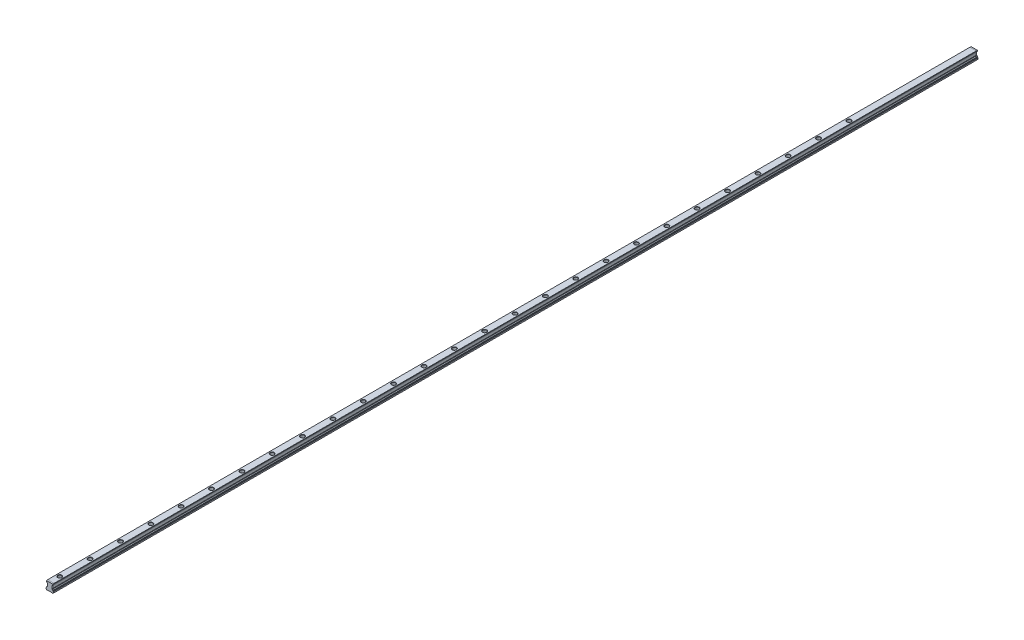
SolidWorks part; units mm, degrees
ref_plane "Front Plane" through (0, 0, 0) normal (0, 0, 1) x (1, 0, 0)
ref_plane "Top Plane" through (0, 0, 0) normal (0, 1, 0) x (1, 0, 0)
ref_plane "Right Plane" through (0, 0, 0) normal (1, 0, 0) x (0, 0, -1)
sketch "Sketch1" plane through (0, 0, 0) normal (0, 0, 1) x (1, 0, 0)
  line L0 (-4.6097, 4.7709) -> (-5.3042, 5.1719)
  line L1 (-4.6097, -0.4291) -> (-4.6097, 4.7709)
  line L2 (-5.3042, -0.83) -> (-4.6097, -0.4291)
  line L3 (-6.6597, -3.5791) -> (-6.6597, -2.0646)
  line L4 (-7.3597, -3.9832) -> (-6.6597, -3.5791)
  line L5 (-7.3597, -6.4791) -> (-7.3597, -3.9832)
  line L6 (-6.1597, -7.6791) -> (-7.3597, -6.4791)
  line L7 (-3.1597, -7.6791) -> (-6.1597, -7.6791)
  line L8 (-2.8597, -7.3791) -> (-3.1597, -7.6791)
  line L9 (3.1403, -7.3791) -> (-2.8597, -7.3791)
  line L10 (3.4403, -7.6791) -> (3.1403, -7.3791)
  line L11 (6.4403, -7.6791) -> (3.4403, -7.6791)
  line L12 (7.6403, -6.4791) -> (6.4403, -7.6791)
  line L13 (7.6403, -3.9832) -> (7.6403, -6.4791)
  line L14 (6.9403, -3.5791) -> (7.6403, -3.9832)
  line L15 (6.9403, -2.0646) -> (6.9403, -3.5791)
  line L16 (4.8903, -0.4291) -> (5.5848, -0.83)
  line L17 (4.8903, 4.7709) -> (4.8903, -0.4291)
  line L18 (5.5848, 5.1719) -> (4.8903, 4.7709)
  line L19 (6.9403, 8.0259) -> (6.9403, 6.4065)
  line L20 (6.4453, 8.5209) -> (6.9403, 8.0259)
  line L21 (-6.1647, 8.5209) -> (6.4453, 8.5209)
  line L22 (-6.6597, 8.0259) -> (-6.1647, 8.5209)
  line L23 (-6.6597, 6.4065) -> (-6.6597, 8.0259)
  arc A0 (-5.3042, 5.1719) -> (-6.6597, 6.4065) centre (-6.9057, 4.7749) ccw
  arc A1 (-6.6597, -2.0646) -> (-5.3042, -0.83) centre (-6.9057, -0.4331) ccw
  arc A2 (5.5848, -0.83) -> (6.9403, -2.0646) centre (7.1863, -0.4331) ccw
  arc A3 (6.9403, 6.4065) -> (5.5848, 5.1719) centre (7.1863, 4.7749) ccw
  dimension "Rail Height" = 16.2
  dimension "Rail Width" = 15
sketch "Sketch2" plane through (0, 0, 0) normal (1, 0, 0) x (0, 0, -1)
  line L0 (-914, 0) -> (914, 0) construction
  line L1 (-774, 0) -> (-774, -10.3) construction
  point P0 (-894, 0)
  point P4 (0, 0)
  point P6 (-834, 0)
  point P7 (-774, 0)
  point P9 (-714, 0)
  point P10 (-654, 0)
  point P11 (-594, 0)
  point P12 (-534, 0)
  point P13 (-474, 0)
  point P14 (-414, 0)
  point P15 (-354, 0)
  point P16 (-294, 0)
  point P17 (-234, 0)
  point P18 (-174, 0)
  point P19 (-114, 0)
  point P20 (-54, 0)
  point P21 (6, 0)
  point P22 (66, 0)
  point P23 (126, 0)
  point P24 (186, 0)
  point P25 (246, 0)
  point P26 (306, 0)
  point P27 (366, 0)
  point P28 (426, 0)
  point P29 (486, 0)
  point P30 (546, 0)
  point P31 (606, 0)
  point P32 (666, 0)
  dimension "Rail Length" = 1828
  dimension "Mounting Hole Center to End" = 20
  dimension "Mounting Hole Center to Center" = 60
  dimension "Mounting Hole Depth" = 10.3
  dimension "Number of Mounting Holes" = 27
sketch "Sketch3" plane through (0, 0, 0) normal (0, 0, 1) x (1, 0, 0)
  line L24 (6.4403, -7.6791) -> (7.6403, -6.4791)
  line L25 (7.6403, -6.4791) -> (7.6403, -3.9832)
  line L26 (7.6403, -3.9832) -> (6.9403, -3.5791)
  line L27 (6.9403, -3.5791) -> (6.9403, -2.0646)
  line L28 (5.5848, -0.83) -> (4.8903, -0.4291)
  line L29 (4.8903, -0.4291) -> (4.8903, 4.7709)
  line L30 (4.8903, 4.7709) -> (5.5848, 5.1719)
  line L31 (6.9403, 6.4065) -> (6.9403, 8.0259)
  line L32 (6.9403, 8.0259) -> (6.4453, 8.5209)
  line L33 (6.4453, 8.5209) -> (-6.1647, 8.5209)
  line L34 (-6.1647, 8.5209) -> (-6.6597, 8.0259)
  line L35 (-6.6597, 8.0259) -> (-6.6597, 6.4065)
  line L36 (-5.3042, 5.1719) -> (-4.6097, 4.7709)
  line L37 (-4.6097, 4.7709) -> (-4.6097, -0.4291)
  line L38 (-4.6097, -0.4291) -> (-5.3042, -0.83)
  line L39 (-6.6597, -2.0646) -> (-6.6597, -3.5791)
  line L40 (-6.6597, -3.5791) -> (-7.3597, -3.9832)
  line L41 (-7.3597, -3.9832) -> (-7.3597, -6.4791)
  line L42 (-7.3597, -6.4791) -> (-6.1597, -7.6791)
  line L43 (-6.1597, -7.6791) -> (-3.1597, -7.6791)
  line L44 (-3.1597, -7.6791) -> (-2.8597, -7.3791)
  line L45 (-2.8597, -7.3791) -> (3.1403, -7.3791)
  line L46 (3.1403, -7.3791) -> (3.4403, -7.6791)
  line L47 (3.4403, -7.6791) -> (6.4403, -7.6791)
  line L48 (6.4403, -7.6791) -> (7.6403, -6.4791)
  line L49 (7.6403, -6.4791) -> (7.6403, -3.9832)
  line L50 (7.6403, -3.9832) -> (6.9403, -3.5791)
  line L51 (6.9403, -3.5791) -> (6.9403, -2.0646)
  line L52 (5.5848, -0.83) -> (4.8903, -0.4291)
  line L53 (4.8903, -0.4291) -> (4.8903, 4.7709)
  line L54 (4.8903, 4.7709) -> (5.5848, 5.1719)
  line L55 (6.9403, 6.4065) -> (6.9403, 8.0259)
  line L56 (6.9403, 8.0259) -> (6.4453, 8.5209)
  line L57 (6.4453, 8.5209) -> (-6.1647, 8.5209)
  line L58 (-6.1647, 8.5209) -> (-6.6597, 8.0259)
  line L59 (-6.6597, 8.0259) -> (-6.6597, 6.4065)
  line L60 (-5.3042, 5.1719) -> (-4.6097, 4.7709)
  line L61 (-4.6097, 4.7709) -> (-4.6097, -0.4291)
  line L62 (-4.6097, -0.4291) -> (-5.3042, -0.83)
  line L63 (-6.6597, -2.0646) -> (-6.6597, -3.5791)
  line L64 (-6.6597, -3.5791) -> (-7.3597, -3.9832)
  line L65 (-7.3597, -3.9832) -> (-7.3597, -6.4791)
  line L66 (-7.3597, -6.4791) -> (-6.1597, -7.6791)
  line L67 (-6.1597, -7.6791) -> (-3.1597, -7.6791)
  line L68 (-3.1597, -7.6791) -> (-2.8597, -7.3791)
  line L69 (-2.8597, -7.3791) -> (3.1403, -7.3791)
  line L70 (3.1403, -7.3791) -> (3.4403, -7.6791)
  line L71 (3.4403, -7.6791) -> (6.4403, -7.6791)
  arc A4 (5.5848, -0.83) -> (6.9403, -2.0646) centre (7.1863, -0.4331) ccw
  arc A5 (6.9403, 6.4065) -> (5.5848, 5.1719) centre (7.1863, 4.7749) ccw
  arc A6 (-5.3042, 5.1719) -> (-6.6597, 6.4065) centre (-6.9057, 4.7749) ccw
  arc A7 (-6.6597, -2.0646) -> (-5.3042, -0.83) centre (-6.9057, -0.4331) ccw
  arc A8 (5.5848, -0.83) -> (6.9403, -2.0646) centre (7.1863, -0.4331) ccw
  arc A9 (6.9403, 6.4065) -> (5.5848, 5.1719) centre (7.1863, 4.7749) ccw
  arc A10 (-5.3042, 5.1719) -> (-6.6597, 6.4065) centre (-6.9057, 4.7749) ccw
  arc A11 (-6.6597, -2.0646) -> (-5.3042, -0.83) centre (-6.9057, -0.4331) ccw
  dimension "D1" = 0
extrude "Boss-Extrude1" add sketch "Sketch3" along normal mid plane 1823
sketch "Sketch4" plane through (0, 0, 911.5) normal (0, 0, 1) x (1, 0, 0)
  line L24 (6.4403, -7.6791) -> (7.6403, -6.4791)
  line L25 (7.6403, -6.4791) -> (7.6403, -3.9832)
  line L26 (7.6403, -3.9832) -> (6.9403, -3.5791)
  line L27 (6.9403, -3.5791) -> (6.9403, -2.0646)
  line L28 (5.5848, -0.83) -> (4.8903, -0.4291)
  line L29 (4.8903, -0.4291) -> (4.8903, 4.7709)
  line L30 (4.8903, 4.7709) -> (5.5848, 5.1719)
  line L31 (6.9403, 6.4065) -> (6.9403, 8.0259)
  line L32 (6.9403, 8.0259) -> (6.4453, 8.5209)
  line L33 (6.4453, 8.5209) -> (-6.1647, 8.5209)
  line L34 (-6.1647, 8.5209) -> (-6.6597, 8.0259)
  line L35 (-6.6597, 8.0259) -> (-6.6597, 6.4065)
  line L36 (-5.3042, 5.1719) -> (-4.6097, 4.7709)
  line L37 (-4.6097, 4.7709) -> (-4.6097, -0.4291)
  line L38 (-4.6097, -0.4291) -> (-5.3042, -0.83)
  line L39 (-6.6597, -2.0646) -> (-6.6597, -3.5791)
  line L40 (-6.6597, -3.5791) -> (-7.3597, -3.9832)
  line L41 (-7.3597, -3.9832) -> (-7.3597, -6.4791)
  line L42 (-7.3597, -6.4791) -> (-6.1597, -7.6791)
  line L43 (-6.1597, -7.6791) -> (-3.1597, -7.6791)
  line L44 (-3.1597, -7.6791) -> (-2.8597, -7.3791)
  line L45 (-2.8597, -7.3791) -> (3.1403, -7.3791)
  line L46 (3.1403, -7.3791) -> (3.4403, -7.6791)
  line L47 (3.4403, -7.6791) -> (6.4403, -7.6791)
  line L48 (6.4403, -7.6791) -> (7.6403, -6.4791)
  line L49 (7.6403, -6.4791) -> (7.6403, -3.9832)
  line L50 (7.6403, -3.9832) -> (6.9403, -3.5791)
  line L51 (6.9403, -3.5791) -> (6.9403, -2.0646)
  line L52 (5.5848, -0.83) -> (4.8903, -0.4291)
  line L53 (4.8903, -0.4291) -> (4.8903, 4.7709)
  line L54 (4.8903, 4.7709) -> (5.5848, 5.1719)
  line L55 (6.9403, 6.4065) -> (6.9403, 8.0259)
  line L56 (6.9403, 8.0259) -> (6.4453, 8.5209)
  line L57 (6.4453, 8.5209) -> (-6.1647, 8.5209)
  line L58 (-6.1647, 8.5209) -> (-6.6597, 8.0259)
  line L59 (-6.6597, 8.0259) -> (-6.6597, 6.4065)
  line L60 (-5.3042, 5.1719) -> (-4.6097, 4.7709)
  line L61 (-4.6097, 4.7709) -> (-4.6097, -0.4291)
  line L62 (-4.6097, -0.4291) -> (-5.3042, -0.83)
  line L63 (-6.6597, -2.0646) -> (-6.6597, -3.5791)
  line L64 (-6.6597, -3.5791) -> (-7.3597, -3.9832)
  line L65 (-7.3597, -3.9832) -> (-7.3597, -6.4791)
  line L66 (-7.3597, -6.4791) -> (-6.1597, -7.6791)
  line L67 (-6.1597, -7.6791) -> (-3.1597, -7.6791)
  line L68 (-3.1597, -7.6791) -> (-2.8597, -7.3791)
  line L69 (-2.8597, -7.3791) -> (3.1403, -7.3791)
  line L70 (3.1403, -7.3791) -> (3.4403, -7.6791)
  line L71 (3.4403, -7.6791) -> (6.4403, -7.6791)
  arc A4 (5.5848, -0.83) -> (6.9403, -2.0646) centre (7.1863, -0.4331) ccw
  arc A5 (6.9403, 6.4065) -> (5.5848, 5.1719) centre (7.1863, 4.7749) ccw
  arc A6 (-5.3042, 5.1719) -> (-6.6597, 6.4065) centre (-6.9057, 4.7749) ccw
  arc A7 (-6.6597, -2.0646) -> (-5.3042, -0.83) centre (-6.9057, -0.4331) ccw
  arc A8 (5.5848, -0.83) -> (6.9403, -2.0646) centre (7.1863, -0.4331) ccw
  arc A9 (6.9403, 6.4065) -> (5.5848, 5.1719) centre (7.1863, 4.7749) ccw
  arc A10 (-5.3042, 5.1719) -> (-6.6597, 6.4065) centre (-6.9057, 4.7749) ccw
  arc A11 (-6.6597, -2.0646) -> (-5.3042, -0.83) centre (-6.9057, -0.4331) ccw
  dimension "D1" = 0
extrude "Boss-Extrude2" add sketch "Sketch4" along normal blind 2.5 draft 7
mirror "Mirror1" about plane through (0, 0, 0) normal (0, 0, 1) of "Boss-Extrude2"
sketch "Sketch5" plane through (0, 8.5209, 0) normal (0, 1, 0) x (1, 0, 0)
  line L0 (6.3182, -914) -> (-6.0376, -914) construction
  line L1 (6.4453, -911.5) -> (-6.1647, -911.5) construction
  circle A0 centre (0.1403, -894) radius 2.25
  point P6 (0.1403, -911.5)
  dimension "D1" = 4.5
  dimension "D2" = 20
extrude "Cut-Extrude1" cut sketch "Sketch5" against normal through all
chamfer "Chamfer1" distance 0.5 1 edges at (0.1403, -7.3791, 896.25)
pattern_linear "LPattern1" count 27 spacing 60 along (0, 0, -1) of "Cut-Extrude1", "Chamfer1"
sketch "Sketch6" plane through (0, 8.5209, 0) normal (0, 1, 0) x (1, 0, 0)
  circle A0 centre (0.1403, -894) radius 3.7
  dimension "D1" = 7.4
extrude "Cut-Extrude2" cut sketch "Sketch6" against normal blind 5.9
chamfer "Chamfer2" distance 0.5 1 edges at (0.1403, 8.5209, 897.7)
pattern_linear "LPattern2" count 27 spacing 60 along (0, 0, -1) of "Cut-Extrude2", "Chamfer2"
sketch "Ref" plane through (4.8903, 0, 0) normal (1, 0, 0) x (0, 0, -1)
  line L0 (-911.5, 8.5209) -> (911.5, 8.5209) construction
  line L1 (-894, 2.6209) -> (-894, 8.5209) construction
  line L2 (-890.3, 2.6209) -> (-897.7, 2.6209) construction
  line L3 (-911.5, -0.4291) -> (911.5, -0.4291) construction
  line L4 (-914, -0.6063) -> (-914, 4.9481) construction
  line L5 (914, -0.6063) -> (914, 4.9481) construction
  line L6 (-890.3, 2.6209) -> (-890.3, 8.0209) construction
  line L7 (-897.7, 8.0209) -> (-897.7, 2.6209) construction
  line L8 (-896.25, 2.6209) -> (-896.25, -6.8791) construction
  line L9 (-891.75, -6.8791) -> (-891.75, 2.6209) construction
  line L10 (911.5, -0.4291) -> (911.5, 4.7709)
  line L11 (911.5, 4.7709) -> (-911.5, 4.7709)
  line L12 (-911.5, 4.7709) -> (-911.5, -0.4291)
  line L13 (-911.5, -0.4291) -> (911.5, -0.4291)
  line L14 (911.5, -0.4291) -> (911.5, 4.7709)
  line L15 (911.5, 4.7709) -> (-911.5, 4.7709) construction
  line L16 (-911.5, 4.7709) -> (-911.5, -0.4291)
  line L18 (-890.3, 2.6209) -> (-890.3, 8.0209) construction
  line L19 (-897.7, 8.0209) -> (-897.7, 2.6209) construction
  line L20 (-896.25, 2.6209) -> (-896.25, -6.8791) construction
  line L21 (-890.3, 2.6209) -> (-897.7, 2.6209) construction
  line L22 (-891.75, -6.8791) -> (-891.75, 2.6209) construction
  line L33 (890.3, 8.5209) -> (890.3, 2.6209) construction
  line L34 (890.3, 2.6209) -> (897.7, 2.6209) construction
  line L35 (897.7, 2.6209) -> (897.7, 8.5209) construction
  line L36 (891.75, 2.6209) -> (891.75, -7.6791) construction
  line L37 (896.25, 2.6209) -> (896.25, -7.6791) construction
  line L38 (894, 2.6209) -> (894, 8.5209) construction
  line L39 (914, 6.6521) -> (914, 7.8988) construction
  point P0 (-894, 8.5209)
  point P7 (-909, -0.4291)
  point P12 (909, -0.4291)
  dimension "D1" = 5
  dimension "D2" = 5
  dimension "D4" = 7.4
  dimension "D5" = 5.9
  dimension "D6" = 10.3
  dimension "D7" = 20
  dimension "D8" = 4.5
  dimension "D3" = 0
equation "\"D1@Boss-Extrude1\"=\"Rail Length@Sketch2\"-5"
equation "\"D3@LPattern1\"=\"Mounting Hole Center to Center@Sketch2\""
equation "\"D1@LPattern1\"=\"Number of Mounting Holes@Sketch2\""
equation "\"D1@Cut-Extrude2\"=\"Rail Height@Sketch1\"-\"Mounting Hole Depth@Sketch2\""
equation "\"D1@LPattern2\"=\"Number of Mounting Holes@Sketch2\""
